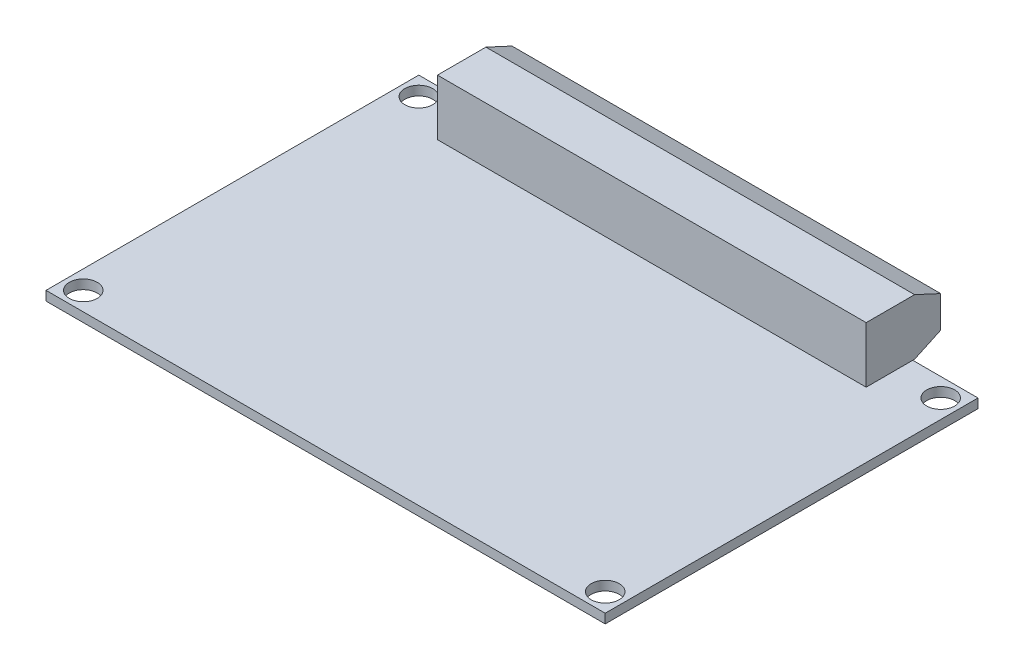
SolidWorks part; units mm, degrees
ref_plane "Front Plane" through (0, 0, 0) normal (0, 0, 1) x (1, 0, 0)
ref_plane "Top Plane" through (0, 0, 0) normal (0, 1, 0) x (1, 0, 0)
ref_plane "Right Plane" through (0, 0, 0) normal (1, 0, 0) x (0, 0, -1)
sketch "Sketch1" plane through (0, 0, 0) normal (0, 1, 0) x (1, 0, 0)
  line L1 (-30, -20) -> (30, -20)
  line L2 (-30, -20) -> (-30, 20)
  line L3 (-30, 20) -> (30, 20)
  line L4 (30, -20) -> (30, 20)
  line L5 (-30, -20) -> (30, 20) construction
  line L6 (-30, 20) -> (30, -20) construction
  point P0 (0, 0)
  dimension "D1" = 60
  dimension "D2" = 40
extrude "Boss-Extrude1" add sketch "Sketch1" along normal mid plane 1
sketch "Sketch2" plane through (0, 0.5, 0) normal (0, 1, 0) x (1, 0, 0)
  line L0 (30, 20) -> (-30, 20) construction
  line L1 (-30, 20) -> (-30, -20) construction
  line L2 (0, 25.9291) -> (0, 0) construction
  line L3 (0, 0) -> (-13.9468, 0) construction
  circle A0 centre (-28, 18) radius 1.5
  circle A1 centre (28, 18) radius 1.5
  circle A2 centre (28, -18) radius 1.5
  circle A3 centre (-28, -18) radius 1.5
  dimension "D1" = 3
  dimension "D2" = 2
  dimension "D3" = 2
extrude "Cut-Extrude1" cut sketch "Sketch2" against normal blind 1
sketch "Sketch3" plane through (0, 0.5, 0) normal (0, 1, 0) x (1, 0, 0)
  line L0 (30, -20) -> (30, 20) construction
  line L1 (-23, 23) -> (23, 23)
  line L2 (-23, 23) -> (-23, 15)
  line L3 (-23, 15) -> (23, 15)
  line L4 (23, 23) -> (23, 15)
  line L6 (30, 20) -> (-30, 20) construction
  dimension "D1" = 8
  dimension "D2" = 46
  dimension "D3" = 7
  dimension "D4" = 3
extrude "Boss-Extrude2" add sketch "Sketch3" along normal blind 6
sketch "Sketch4" plane through (23, 0, 0) normal (1, 0, 0) x (0, 0, -1)
  line L0 (23, 5.2) -> (23, 6.5)
  line L1 (23, 6.5) -> (23, 0.5) construction
  line L2 (23, 6.5) -> (20.2, 6.5)
  line L3 (15, 6.5) -> (23, 6.5) construction
  line L4 (20.2, 6.5) -> (23, 5.2)
  line L5 (23, 3.5) -> (28.1144, 3.5) construction
  line L6 (20.2, 0.5) -> (23, 1.8)
  line L7 (23, 0.5) -> (20.2, 0.5)
  line L8 (23, 1.8) -> (23, 0.5)
  dimension "D1" = 1.3
  dimension "D2" = 2.8
extrude "Cut-Extrude2" cut sketch "Sketch4" against normal through all
